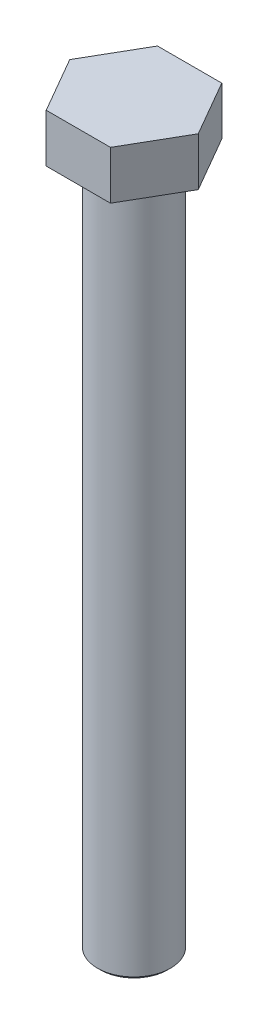
SolidWorks part; units mm, degrees
material "Plain Carbon Steel"
ref_plane "Front Plane" through (0, 0, 0) normal (0, 0, 1) x (1, 0, 0)
ref_plane "Top Plane" through (0, 0, 0) normal (0, 1, 0) x (1, 0, 0)
ref_plane "Right Plane" through (0, 0, 0) normal (1, 0, 0) x (0, 0, -1)
sketch "Sketch1" plane through (0, 0, 0) normal (0, 1, 0) x (1, 0, 0)
  line L0 (0, 0) -> (9.6703, 0) construction
  line L1 (8.2636, 0) -> (4.1318, 7.1565)
  line L2 (4.1318, 7.1565) -> (-4.1318, 7.1565)
  line L3 (-4.1318, 7.1565) -> (-8.2636, 0)
  line L4 (-8.2636, 0) -> (-4.1318, -7.1564)
  line L5 (-4.1318, -7.1564) -> (4.1318, -7.1564)
  line L6 (4.1318, -7.1564) -> (8.2636, 0)
  circle A0 centre (0, 0) radius 7.1564 construction
  dimension "D1" = 14.3129
extrude "Extrude1" add sketch "Sketch1" against normal blind 6.223
sketch "Sketch2" plane through (0, -6.223, 0) normal (0, -1, 0) x (1, 0, 0)
  circle A0 centre (0, 0) radius 4.699
  dimension "D1" = 9.398
extrude "Extrude2" add sketch "Sketch2" along normal blind 88.9
chamfer "Chamfer1" distance 0.3962 angle 45 1 edges at (0, -95.123, -4.699)
